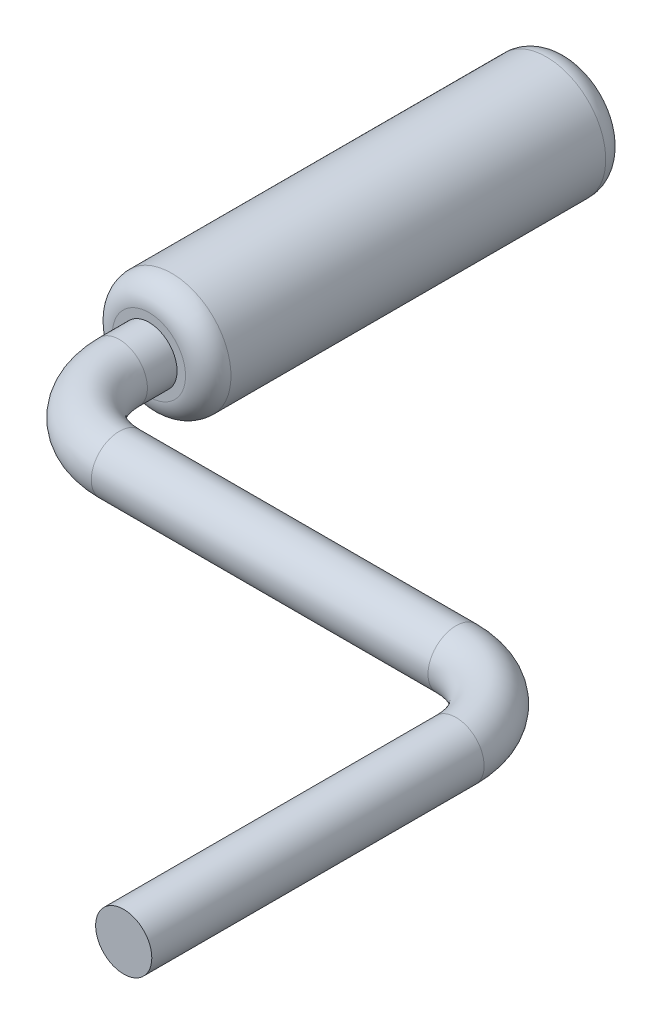
SolidWorks part; units mm, degrees
ref_plane "Front Plane" through (0, 0, 0) normal (0, 0, 1) x (1, 0, 0)
ref_plane "Top Plane" through (0, 0, 0) normal (0, 1, 0) x (1, 0, 0)
ref_plane "Right Plane" through (0, 0, 0) normal (1, 0, 0) x (0, 0, -1)
sketch3d "3DSketch2"
  line L0 (-101.8637, 710.9852, -786.8645) -> (-101.8637, 710.9852, -861.2022)
  line L1 (-119.6437, 710.9852, -878.9822) -> (-194.959, 710.9852, -878.9822)
  line L2 (-212.739, 710.9852, -896.7622) -> (-212.739, 710.9852, -997.3762)
  arc A0 (-86.8716, 713.4903, -786.8645) -> (-101.7011, 726.1843, -786.8645) centre (-101.8637, 710.9852, -786.8645) ccw construction
  arc A1 (-101.8637, 710.9852, -861.2022) -> (-119.6437, 710.9852, -878.9822) centre (-119.6437, 710.9852, -861.2022) ccw
  arc A2 (-194.959, 710.9852, -878.9822) -> (-212.739, 710.9852, -896.7622) centre (-194.959, 710.9852, -896.7622) ccw
  point P5 (-101.8637, 710.9852, -771.6645)
  point P10 (-101.8637, 710.9852, -878.9822)
  point P11 (-119.6437, 728.7652, -861.2022)
  point P14 (-212.739, 710.9852, -878.9822)
  point P15 (-194.959, 693.2052, -896.7622)
  dimension "D1" = 17.78
  dimension "D2" = 17.78
ref_plane "Plane1" through (-212.739, 710.9852, -997.3762) normal (0, 0, -1) x (-1, 0, 0)
sketch "Sketch2" plane through (-212.739, 710.9852, -997.3762) normal (0, 0, -1) x (-1, 0, 0)
  circle A0 centre (0, 0) radius 6.2817
sweep "Sweep1" add profiles "Sketch2" path "3DSketch2"
sketch "Sketch3" plane through (0, 0, -997.3762) normal (0, 0, -1) x (-1, 0, 0)
  circle A0 centre (212.739, 710.9852) radius 13.257
extrude "Boss-Extrude2" add sketch "Sketch3" against normal blind 93.98
fillet "Fillet1" radius 5.08 2 edges at (-225.9959, 710.9852, -997.3762) (-225.9959, 710.9852, -903.3962)
